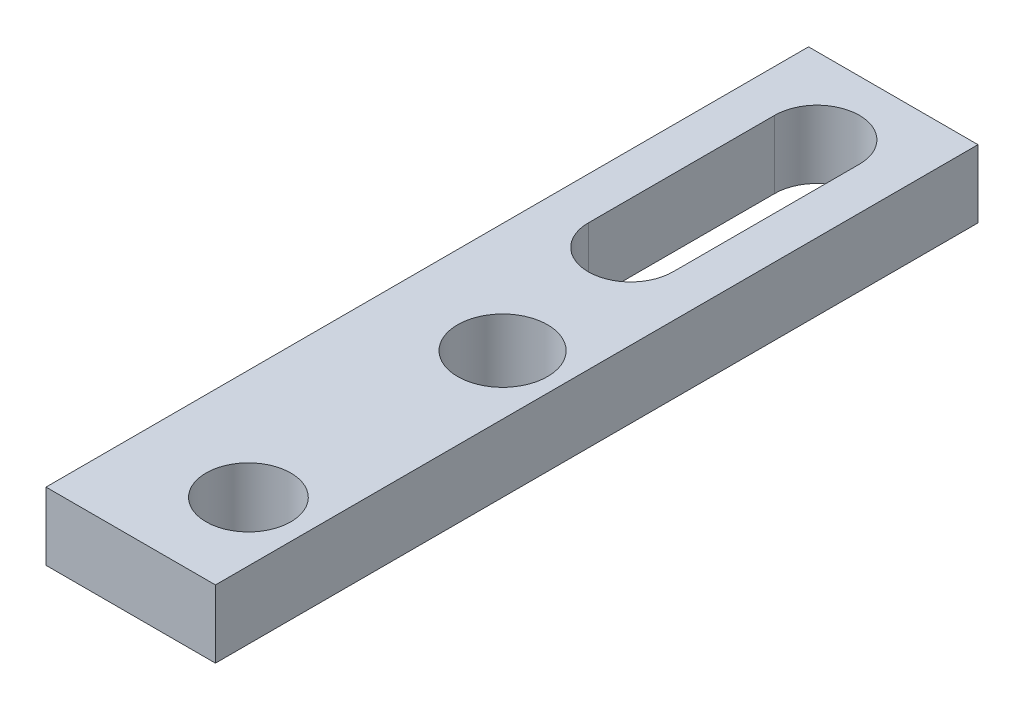
SolidWorks part; units mm, degrees
ref_plane "前基準面" through (0, 0, 0) normal (0, 0, 1) x (1, 0, 0)
ref_plane "上基準面" through (0, 0, 0) normal (0, 1, 0) x (1, 0, 0)
ref_plane "右基準面" through (0, 0, 0) normal (1, 0, 0) x (0, 0, -1)
sketch "草圖1" plane through (0, 0, 0) normal (0, 1, 0) x (1, 0, 0)
  line L0 (0, 18) -> (0, 7) construction
  line L1 (5, 22.5) -> (-5, 22.5)
  line L2 (5, 22.5) -> (5, -22.5)
  line L3 (5, -22.5) -> (-5, -22.5)
  line L4 (-5, 22.5) -> (-5, -22.5)
  line L6 (5, 0) -> (-5, 0) construction
  line L7 (2.5, 18) -> (2.5, 7)
  line L8 (-2.5, 18) -> (-2.5, 7)
  arc A0 (2.5, 18) -> (-2.5, 18) centre (0, 18) ccw
  arc A1 (-2.5, 7) -> (2.5, 7) centre (0, 7) ccw
  circle A2 centre (1.5, -2.0556) radius 2.6533
  circle A3 centre (1.5, -17.0556) radius 2.5
  point P0 (0, 0)
  point P6 (0, 12.5)
  point P15 (0, 20.5)
  point P16 (0, 4.5)
  dimension "D1" = 10
  dimension "D2" = 5
  dimension "D3" = 15
  dimension "D4" = 45
  dimension "D5" = 2
  dimension "D6" = 16
  dimension "D7" = 3.5
extrude "填料-伸長1" add sketch "草圖1" along normal blind 4
